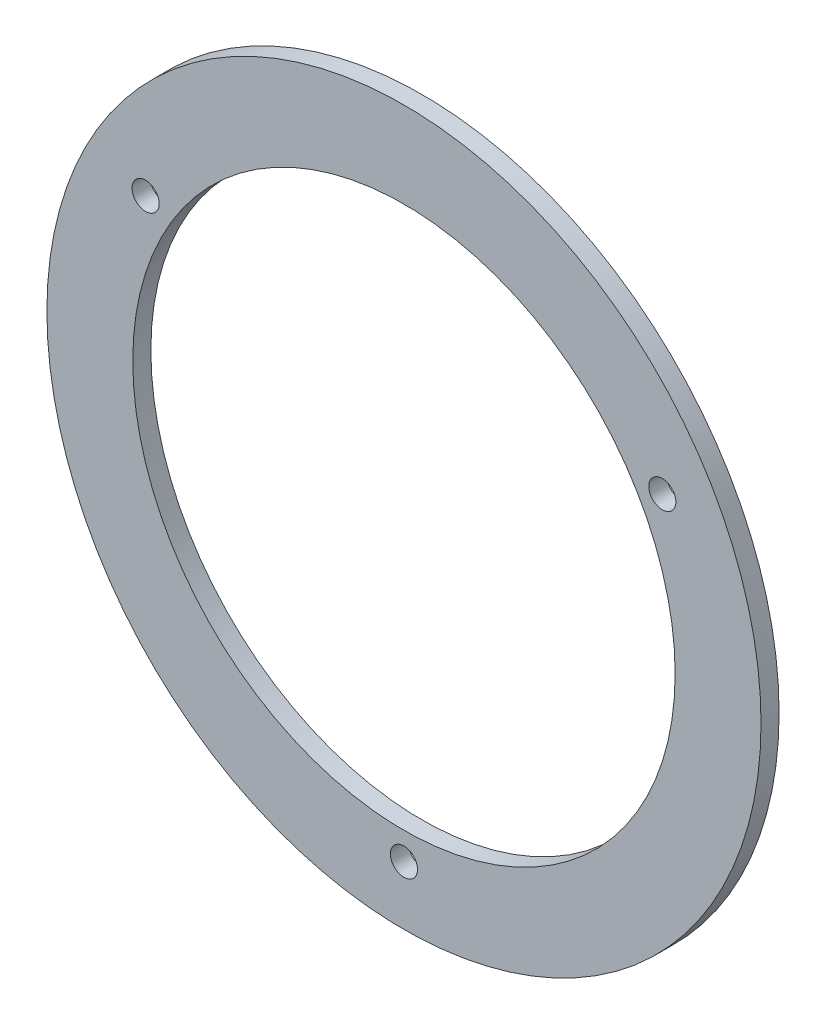
SolidWorks part; units mm, degrees
ref_plane "前视基准面" through (0, 0, 0) normal (0, 0, 1) x (1, 0, 0)
ref_plane "上视基准面" through (0, 0, 0) normal (0, 1, 0) x (1, 0, 0)
ref_plane "右视基准面" through (0, 0, 0) normal (1, 0, 0) x (0, 0, -1)
sketch "草图1" plane through (0, 0, 0) normal (0, 0, 1) x (1, 0, 0)
  circle A0 centre (0, 0) radius 30
  circle A1 centre (0, 0) radius 39.5
extrude "凸台-拉伸1" add sketch "草图1" along normal blind 2
sketch "草图2" plane through (0, 0, 2) normal (0, 0, 1) x (1, 0, 0)
  circle A0 centre (0, -33) radius 1.5
  circle A1 centre (-28.5788, 16.5) radius 1.5
  circle A2 centre (28.5788, 16.5) radius 1.5
  point P9 (0, 0)
  dimension "D1" = 3
extrude "切除-拉伸1" cut sketch "草图2" against normal blind 2
